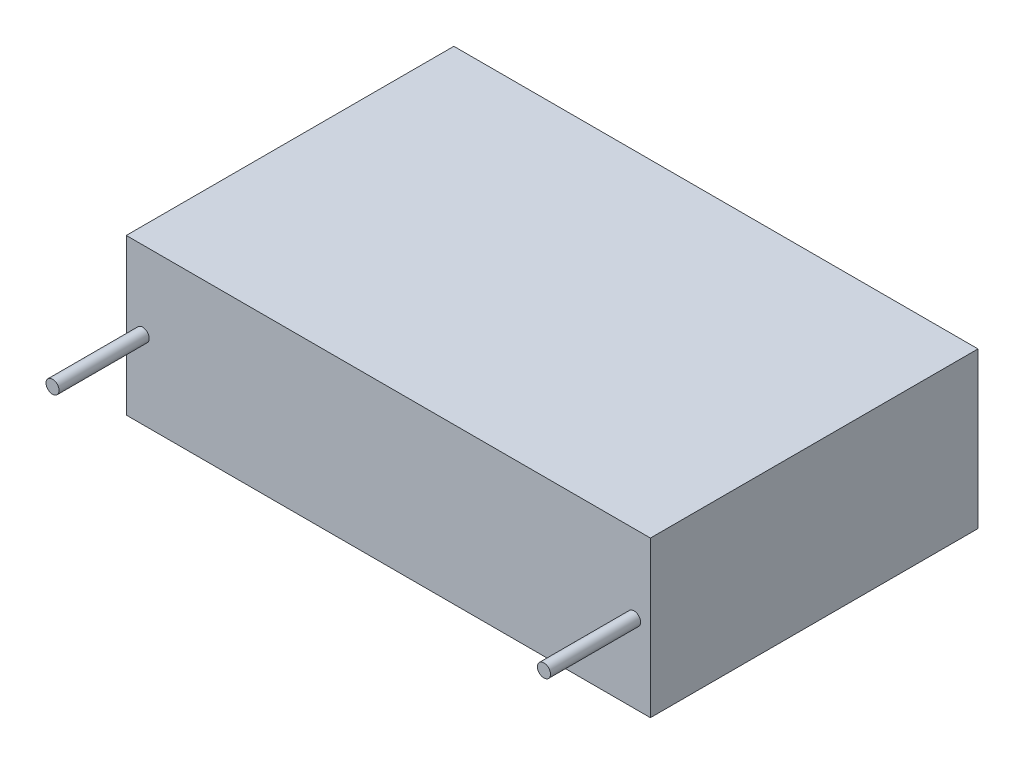
SolidWorks part; units mm, degrees
ref_plane "Спереди" through (0, 0, 0) normal (0, 0, 1) x (1, 0, 0)
ref_plane "Сверху" through (0, 0, 0) normal (0, 1, 0) x (1, 0, 0)
ref_plane "Справа" through (0, 0, 0) normal (1, 0, 0) x (0, 0, -1)
sketch "Эскиз1" plane through (0, 0, 0) normal (0, 0, 1) x (1, 0, 0)
  line L1 (0, 0) -> (32, 0)
  line L2 (0, 0) -> (0, 9.5)
  line L3 (0, 9.5) -> (32, 9.5)
  line L4 (32, 0) -> (32, 9.5)
  dimension "D1" = 9.5
  dimension "D2" = 32
extrude "Вытянуть1" add sketch "Эскиз1" along normal blind 20
sketch "Эскиз2" plane through (0, 0, 20) normal (0, 0, 1) x (1, 0, 0)
  line L0 (-0.6613, 4.75) -> (24.2043, 4.75) construction
  line L1 (0, 0) -> (32, 0) construction
  line L2 (32, 9.5) -> (0, 9.5) construction
  line L3 (16, 10.4113) -> (16, -0.9059) construction
  line L4 (0, 9.5) -> (0, 0) construction
  line L5 (32, 0) -> (32, 9.5) construction
  circle A0 centre (1, 4.75) radius 0.4
  circle A1 centre (31, 4.75) radius 0.4
  dimension "D1" = 30
  dimension "D2" = 0.8
extrude "Вытянуть2" add sketch "Эскиз2" along normal blind 5.5
